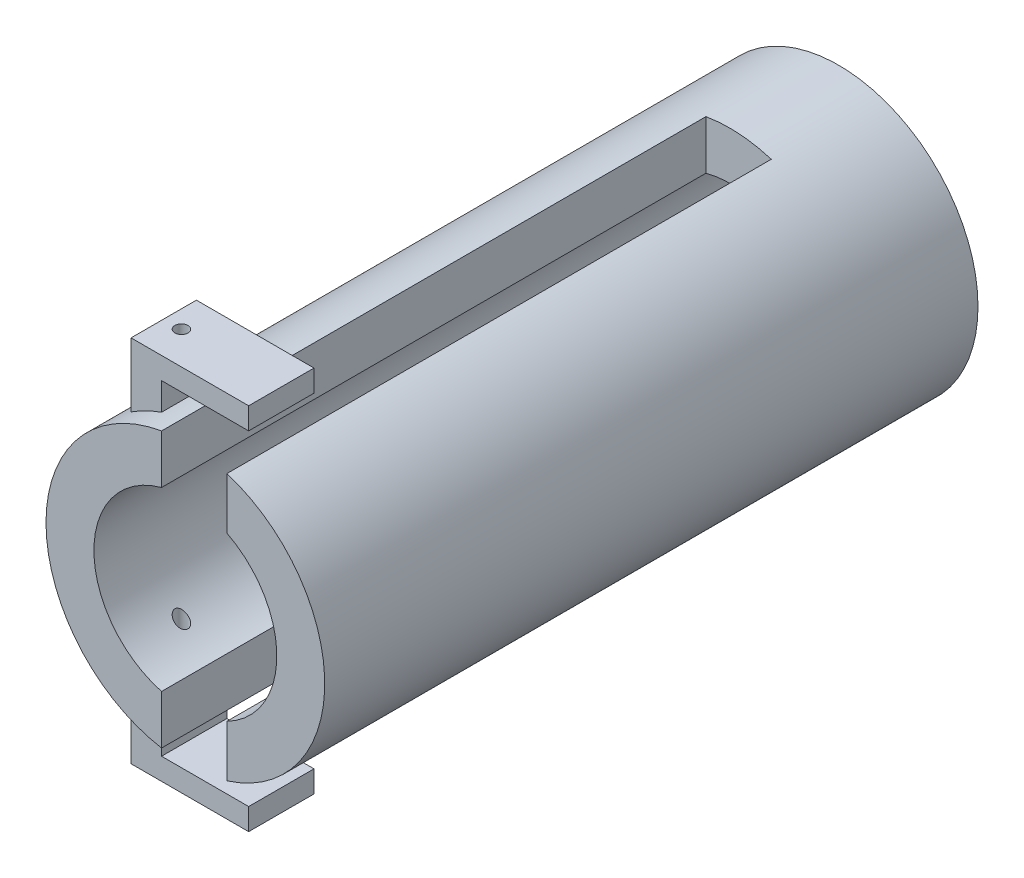
SolidWorks part; units mm, degrees
ref_plane "Plano frontal" through (0, 0, 0) normal (0, 0, 1) x (1, 0, 0)
ref_plane "Plano superior" through (0, 0, 0) normal (0, 1, 0) x (1, 0, 0)
ref_plane "Plano direito" through (0, 0, 0) normal (1, 0, 0) x (0, 0, -1)
sketch "Esboço1" plane through (0, 0, 0) normal (0, 0, 1) x (1, 0, 0)
  circle A0 centre (0, 0) radius 21
  circle A1 centre (0, 0) radius 32
extrude "Ressalto-extrusão1" add sketch "Esboço1" along normal blind 150
sketch3d "3DSketch1"
  point P0 (4.4721, -31.686, 55.7114)
ref_plane "Plano1" through (0, -33.1622, 0) normal (0, -1, 0) x (0, 0, -1)
sketch "Esboço3" plane through (0, -33.1622, 0) normal (0, -1, 0) x (0, 0, -1)
  line L0 (-150, -5.4656) -> (-150, 9.5344)
  line L1 (-150, 32) -> (-150, -32) construction
  line L2 (-150, 9.5344) -> (-25, 9.5344)
  line L3 (-25, 9.5344) -> (-25, -5.4656)
  line L4 (-25, -5.4656) -> (-150, -5.4656)
  line L5 (0, -32) -> (0, 32) construction
  point P5 (-150, 2.0344)
  point P9 (-150, -5.4656)
  dimension "D1" = 15
  dimension "D2" = 25
extrude "Corte-extrusão1" cut sketch "Esboço3" against normal through all both and the other way through all
sketch "Esboço4" plane through (0, -33.1622, 0) normal (0, -1, 0) x (0, 0, -1)
  line L0 (-25, -5.4656) -> (-150, -5.4656) construction
  line L1 (-145, -10.4656) -> (-130, -10.4656)
  line L2 (-145, -10.4656) -> (-145, -17.4656)
  line L3 (-145, -17.4656) -> (-130, -17.4656)
  line L4 (-130, -10.4656) -> (-130, -17.4656)
  line L5 (-150, -5.4656) -> (-150, -32) construction
  dimension "D1" = 5
  dimension "D2" = 5
  dimension "D3" = 15
  dimension "D4" = 7
extrude "Ressalto-extrusão2" add sketch "Esboço4" against normal up to next
sketch "Esboço5" plane through (0, -33.1622, 0) normal (0, -1, 0) x (1, 0, 0)
  line L1 (-10.4656, 145) -> (-17.4656, 145)
  line L2 (-10.4656, 145) -> (-10.4656, 130)
  line L3 (-10.4656, 130) -> (-17.4656, 130)
  line L4 (-17.4656, 145) -> (-17.4656, 130)
extrude "Ressalto-extrusão3" add sketch "Esboço5" along normal blind 10
sketch "Esboço6" plane through (-10.4656, 0, 0) normal (1, 0, 0) x (0, 0, -1)
  line L0 (-130, -30.2402) -> (-130, -43.1622) construction
  line L1 (-145, -43.1622) -> (-130, -43.1622)
  line L2 (-145, -43.1622) -> (-145, -38.1622)
  line L3 (-145, -38.1622) -> (-130, -38.1622)
  line L4 (-130, -43.1622) -> (-130, -38.1622)
  dimension "D1" = 5
extrude "Ressalto-extrusão4" add sketch "Esboço6" along normal blind 20
sketch3d "3DSketch2"
  point P0 (5.4486, 31.5327, 12.7577)
ref_plane "Plano3" through (0, 31.5327, 0) normal (0, 1, 0) x (0, 0, 1)
sketch "Esboço7" plane through (0, 31.5327, 0) normal (0, 1, 0) x (0, 0, 1)
  line L0 (150, -32) -> (150, -5.4656) construction
  line L1 (130, -10.4656) -> (145, -10.4656)
  line L2 (130, -10.4656) -> (130, -17.4656)
  line L3 (130, -17.4656) -> (145, -17.4656)
  line L4 (145, -10.4656) -> (145, -17.4656)
  line L5 (150, -5.4656) -> (25, -5.4656) construction
  dimension "D1" = 15
  dimension "D2" = 5
  dimension "D3" = 5
  dimension "D4" = 7
extrude "Ressalto-extrusão5" add sketch "Esboço7" against normal up to next
sketch "Esboço8" plane through (0, 31.5327, 0) normal (0, 1, 0) x (1, 0, 0)
  line L1 (-17.4656, -130) -> (-10.4656, -130)
  line L2 (-17.4656, -130) -> (-17.4656, -145)
  line L3 (-17.4656, -145) -> (-10.4656, -145)
  line L4 (-10.4656, -130) -> (-10.4656, -145)
extrude "Ressalto-extrusão6" add sketch "Esboço8" along normal blind 10
sketch "Esboço9" plane through (-10.4656, 0, 0) normal (1, 0, 0) x (0, 0, -1)
  line L5 (-130, 30.2402) -> (-130, 41.5327) construction
  line L6 (-145, 41.5327) -> (-130, 41.5327)
  line L7 (-145, 41.5327) -> (-145, 36.5327)
  line L8 (-145, 36.5327) -> (-130, 36.5327)
  line L9 (-130, 41.5327) -> (-130, 36.5327)
  dimension "D1" = 5
extrude "Ressalto-extrusão7" add sketch "Esboço9" along normal blind 20
sketch "Esboço10" plane through (0, -43.1622, 0) normal (0, -1, 0) x (1, 0, 0)
  line L0 (-17.4656, 137.5) -> (9.5344, 137.5) construction
  line L1 (-17.4656, 145) -> (-17.4656, 130) construction
  line L2 (9.5344, 145) -> (9.5344, 130) construction
  circle A0 centre (-13.4052, 137.5) radius 1.5
extrude "Corte-extrusão2" cut sketch "Esboço10" against normal through all both and the other way through all
